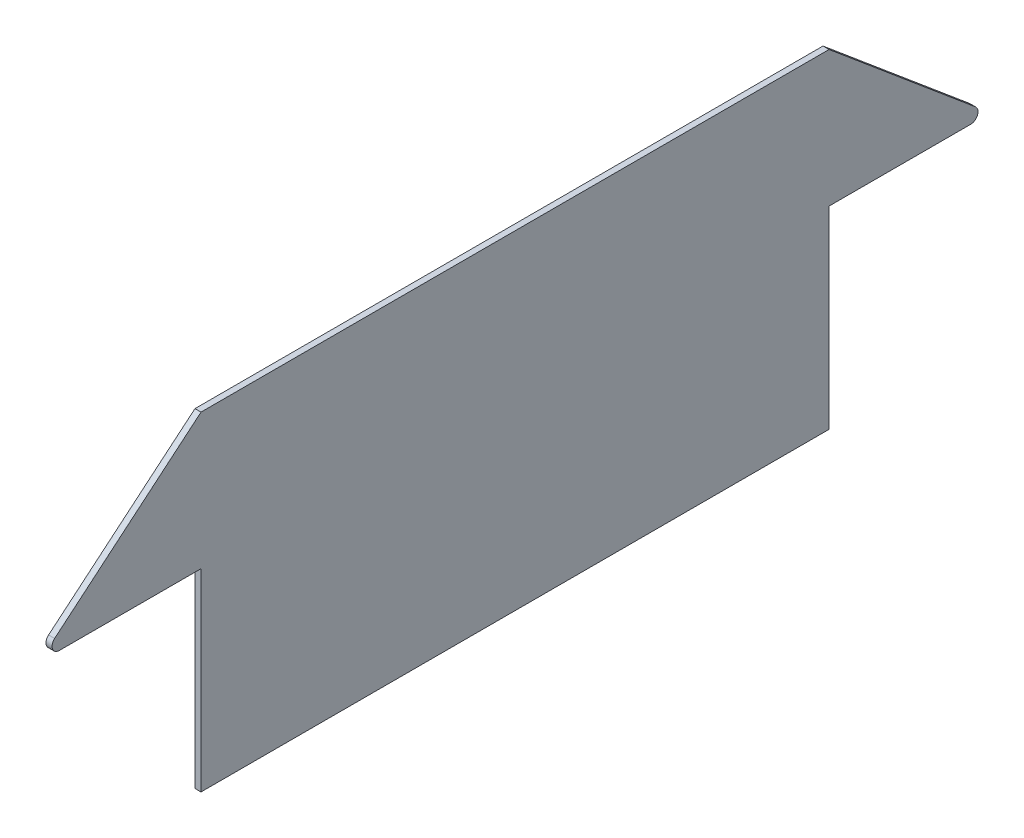
SolidWorks part; units mm, degrees
material "Cedar"
ref_plane "Front Plane" through (0, 0, 0) normal (0, 0, 1) x (1, 0, 0)
ref_plane "Top Plane" through (0, 0, 0) normal (0, 1, 0) x (1, 0, 0)
ref_plane "Right Plane" through (0, 0, 0) normal (1, 0, 0) x (0, 0, -1)
sketch "Sketch1" plane through (0, 0, 0) normal (1, 0, 0) x (0, 0, -1)
  line L0 (330, 101.6) -> (482.4, 101.6)
  line L1 (-330, -101.6) -> (330, -101.6)
  line L2 (-330, -101.6) -> (-330, 101.6)
  line L3 (-330, 101.6) -> (330, 101.6) construction
  line L4 (330, -101.6) -> (330, 101.6)
  line L5 (-330, -101.6) -> (330, 101.6) construction
  line L6 (-330, 101.6) -> (330, -101.6) construction
  line L7 (330, 101.6) -> (330, 107.95) construction
  line L8 (-330, 101.6) -> (-482.4, 101.6)
  line L9 (330, 107.95) -> (482.4, 107.95) construction
  line L10 (482.4, 107.95) -> (482.4, 101.6) construction
  line L11 (482.4, 107.95) -> (486.4817, 112.8144) construction
  line L12 (486.4817, 112.8144) -> (330, 244.1181)
  line L13 (486.4817, 112.8144) -> (330, 112.8144) construction
  line L14 (482.4, 101.6) -> (499.8465, 101.6)
  line L15 (499.8465, 101.6) -> (486.4817, 112.8144)
  line L16 (330, 244.1181) -> (-330, 244.1181)
  line L17 (-330, 244.1181) -> (-499.8465, 101.6)
  line L18 (-499.8465, 101.6) -> (-482.4, 101.6)
  point P0 (0, 0)
  dimension "D1" = 660
  dimension "D2" = 203.2
  dimension "D3" = 152.4
  dimension "D4" = 6.35
  dimension "D5" = 40
extrude "Boss-Extrude1" add sketch "Sketch1" along normal blind 6.35
fillet "Fillet1" radius 7.62 2 edges at (3.175, 101.6, 499.8465) (3.175, 101.6, -499.8465)
sketch "Sketch3" [suppressed] plane through (6.35, 0, 0) normal (1, 0, 0) x (0, 0, -1)
  line L0 (0, 244.1181) -> (0, -101.6) construction
  line L1 (330, 244.1181) -> (-330, 244.1181) construction
  line L2 (-330, -101.6) -> (330, -101.6) construction
  line L3 (-330, 167.9181) -> (330, 167.9181) construction
  line L5 (-330, 101.6) -> (-330, -101.6) construction
  line L6 (330, -101.6) -> (330, 101.6) construction
  text T0 "<b>UCR</b>\r\n<b>Scotty</b>\r\n<b>Bot</b>" font "Courier New" height 63.5
  dimension "D1" = 76.2
extrude "Cut-Extrude1" [suppressed] cut sketch "Sketch3" against normal blind 3.175
